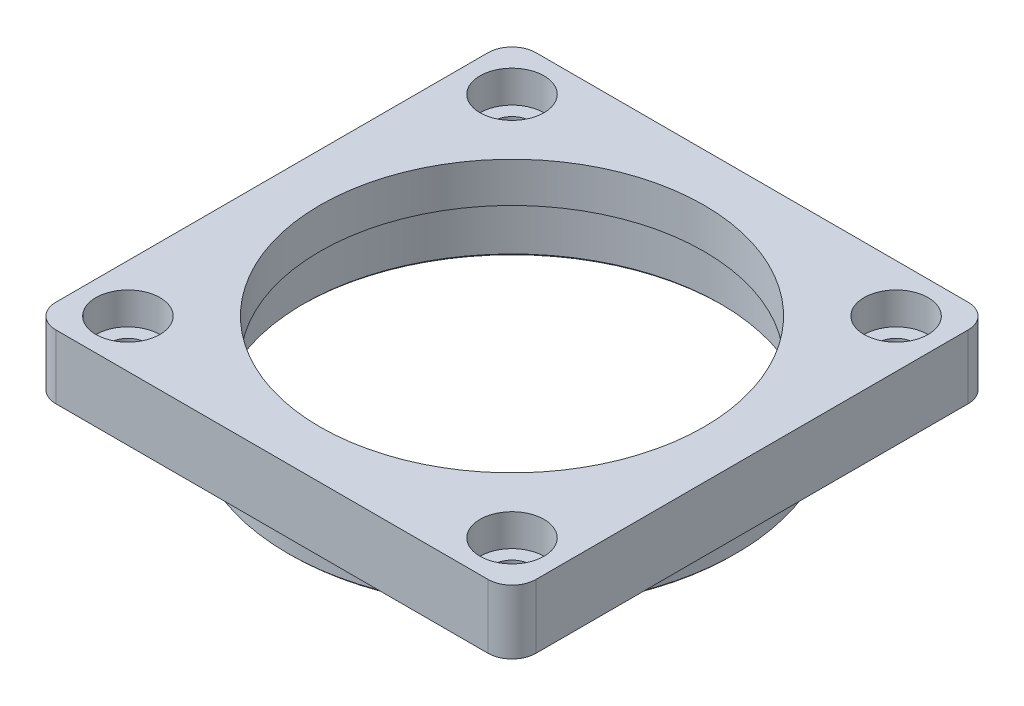
SolidWorks part; units mm, degrees
ref_plane "Спереди" through (0, 0, 0) normal (0, 0, 1) x (1, 0, 0)
ref_plane "Сверху" through (0, 0, 0) normal (0, 1, 0) x (1, 0, 0)
ref_plane "Справа" through (0, 0, 0) normal (1, 0, 0) x (0, 0, -1)
other "Configuration Table"
sketch "Эскиз1" plane through (0, 0, 0) normal (0, 1, 0) x (1, 0, 0)
  line L1 (-30, 30) -> (30, 30)
  line L2 (-30, 30) -> (-30, -30)
  line L3 (-30, -30) -> (30, -30)
  line L4 (30, 30) -> (30, -30)
  line L5 (-30, 30) -> (30, -30) construction
  line L6 (-30, -30) -> (30, 30) construction
  circle A0 centre (0, 0) radius 24
  point P0 (0, 0)
  dimension "D3" = 48
  dimension "D1" = 60
  dimension "D2" = 60
extrude "Бобышка-Вытянуть1" add sketch "Эскиз1" along normal blind 8
sketch "Эскиз2" plane through (0, 0, 0) normal (0, -1, 0) x (1, 0, 0)
  circle A0 centre (0, 0) radius 26
  circle A1 centre (0, 0) radius 28
  dimension "D1" = 56
  dimension "D2" = 52
extrude "Бобышка-Вытянуть2" add sketch "Эскиз2" along normal blind 4
sketch "Эскиз3" plane through (0, 0, 0) normal (0, -1, 0) x (-1, 0, 0)
  circle A0 centre (24, -24) radius 2.25
  circle A1 centre (-24, -24) radius 2.25
  circle A2 centre (-24, 24) radius 2.25
  circle A3 centre (24, 24) radius 2.25
  dimension "D3" = 4.5
  dimension "D1" = 24
  dimension "D2" = 24
  dimension "D4" = 2
  dimension "D5" = 2
extrude "Вырез-Вытянуть1" cut sketch "Эскиз3" against normal through all
fillet "Скругление1" radius 3 4 edges at (-30, 4, 30) (-30, 4, -30) (30, 4, -30) (30, 4, 30)
sketch "Эскиз4" plane through (0, -4, 0) normal (0, -1, 0) x (1, 0, 0)
  circle A0 centre (0, 0) radius 26.05
  dimension "D1" = 52.1
extrude "Вырез-Вытянуть2" cut sketch "Эскиз4" against normal blind 7
sketch "Эскиз5" plane through (0, 8, 0) normal (0, 1, 0) x (1, 0, 0)
  circle A0 centre (-24, 24) radius 4
  circle A1 centre (24, 24) radius 4
  circle A2 centre (24, -24) radius 4
  circle A3 centre (-24, -24) radius 4
  dimension "D1" = 8
  dimension "D2" = 2
  dimension "D3" = 2
extrude "Вырез-Вытянуть3" cut sketch "Эскиз5" against normal blind 4
chamfer "Фаска1" distance 0.3 angle 45 2 edges at (0, -4, -28) (0, -4, -26.05)
